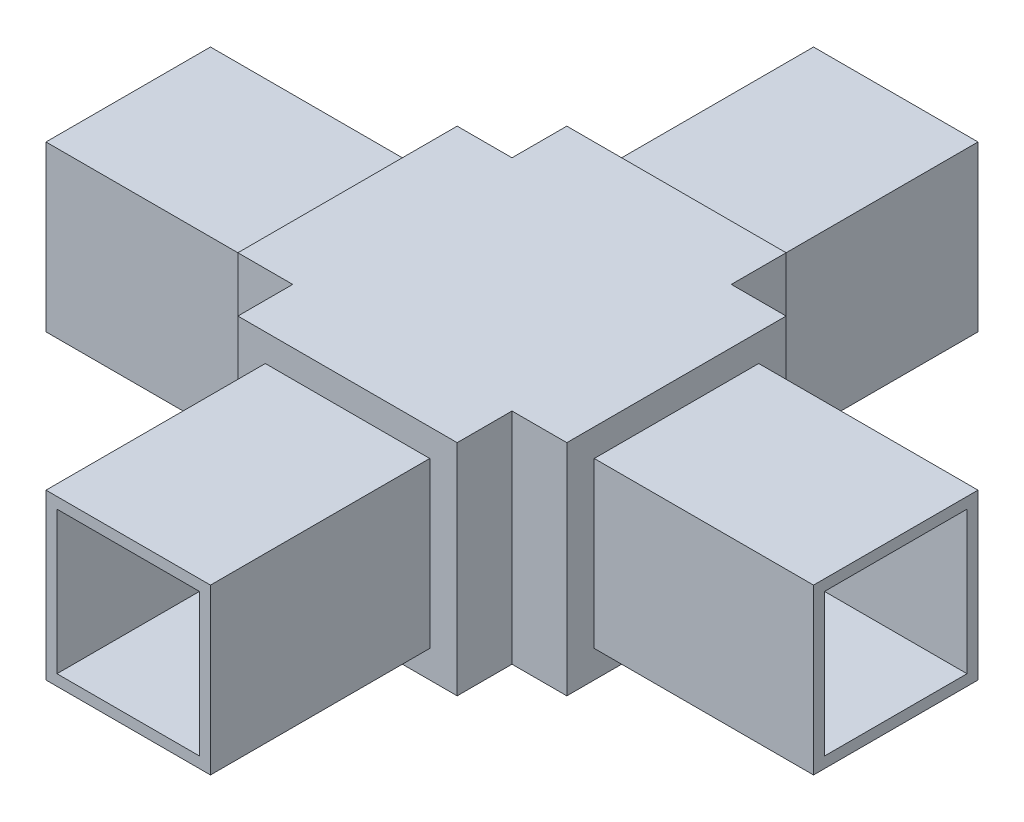
SolidWorks part; units mm, degrees
ref_plane "Alzado" through (0, 0, 0) normal (0, 0, 1) x (1, 0, 0)
ref_plane "Planta" through (0, 0, 0) normal (0, 1, 0) x (1, 0, 0)
ref_plane "Vista lateral" through (0, 0, 0) normal (1, 0, 0) x (0, 0, -1)
sketch "Croquis1" plane through (0, 0, 0) normal (0, 1, 0) x (1, 0, 0)
  line L1 (20, -20) -> (-20, -20)
  line L2 (20, -20) -> (20, 20)
  line L3 (20, 20) -> (-20, 20)
  line L4 (-20, -20) -> (-20, 20)
  line L5 (20, -20) -> (-20, 20) construction
  line L6 (20, 20) -> (-20, -20) construction
  line L7 (20, -20) -> (70, -20)
  line L8 (20, -20) -> (20, 20)
  line L9 (20, 20) -> (70, 20)
  line L10 (70, -20) -> (70, 20)
  line L11 (-20, 20) -> (20, 20)
  line L12 (-20, 20) -> (-20, 70)
  line L13 (-20, 70) -> (20, 70)
  line L14 (20, 20) -> (20, 70)
  line L15 (-20, -20) -> (-70, -20)
  line L16 (-20, -20) -> (-20, 20)
  line L17 (-20, 20) -> (-70, 20)
  line L18 (-70, -20) -> (-70, 20)
  line L19 (-20, -20) -> (20, -20)
  line L20 (-20, -20) -> (-20, -70)
  line L21 (-20, -70) -> (20, -70)
  line L22 (20, -20) -> (20, -70)
  point P0 (0, 0)
  dimension "D1" = 40
  dimension "D2" = 40
  dimension "D3" = 50
  dimension "D4" = 50
  dimension "D5" = 50
  dimension "D6" = 50
extrude "Extruir1" add sketch "Croquis1" along normal blind 40 contours L3 L14 L13 L12 | L4 L1 L2 L3 | L7 L10 L9 L2 | L18 L15 L4 L17 | L22 L1 L20 L21
sketch "Croquis2" plane through (70, 0, 0) normal (1, 0, 0) x (0, 0, -1)
  line L4 (-20, 0) -> (20, 0)
  line L5 (20, 0) -> (20, 40)
  line L6 (20, 40) -> (-20, 40)
  line L7 (-20, 40) -> (-20, 0)
  line L8 (-20, 0) -> (20, 0)
  line L9 (20, 0) -> (20, 40)
  line L10 (20, 40) -> (-20, 40)
  line L11 (-20, 40) -> (-20, 0)
  line L16 (-15, 5) -> (15, 5)
  line L17 (15, 5) -> (15, 35)
  line L18 (15, 35) -> (-15, 35)
  line L19 (-15, 35) -> (-15, 5)
  line L20 (-15, 5) -> (15, 5)
  line L21 (15, 5) -> (15, 35)
  line L22 (15, 35) -> (-15, 35)
  line L23 (-15, 35) -> (-15, 5)
  dimension "D1" = 0
  dimension "D2" = 5
extrude "Extruir2" cut sketch "Croquis2" against normal blind 40
sketch "Croquis3" plane through (0, 0, -70) normal (0, 0, -1) x (-1, 0, 0)
  line L0 (-15, 5) -> (15, 5)
  line L1 (15, 5) -> (15, 35)
  line L2 (15, 35) -> (-15, 35)
  line L3 (-15, 35) -> (-15, 5)
  line L4 (-20, 0) -> (20, 0)
  line L5 (20, 0) -> (20, 40)
  line L6 (20, 40) -> (-20, 40)
  line L7 (-20, 40) -> (-20, 0)
  line L8 (-20, 0) -> (20, 0)
  line L9 (20, 0) -> (20, 40)
  line L10 (20, 40) -> (-20, 40)
  line L11 (-20, 40) -> (-20, 0)
  line L16 (20, 0) -> (20, 40) construction
  dimension "D1" = 0
  dimension "D2" = 5
extrude "Extruir3" cut sketch "Croquis3" against normal blind 40
sketch "Croquis5" plane through (-70, 0, 0) normal (-1, 0, 0) x (0, 0, 1)
  line L0 (-15, 5) -> (15, 5)
  line L1 (15, 5) -> (15, 35)
  line L2 (15, 35) -> (-15, 35)
  line L3 (-15, 35) -> (-15, 5)
  line L4 (-20, 0) -> (20, 0)
  line L5 (20, 0) -> (20, 40)
  line L6 (20, 40) -> (-20, 40)
  line L7 (-20, 40) -> (-20, 0)
  line L8 (-20, 0) -> (20, 0)
  line L9 (20, 0) -> (20, 40)
  line L10 (20, 40) -> (-20, 40)
  line L11 (-20, 40) -> (-20, 0)
  dimension "D1" = 0
  dimension "D2" = 5
extrude "Extruir4" cut sketch "Croquis5" against normal blind 40
sketch "Croquis6" plane through (0, 0, 70) normal (0, 0, 1) x (1, 0, 0)
  line L0 (-15, 5) -> (15, 5)
  line L1 (15, 5) -> (15, 35)
  line L2 (15, 35) -> (-15, 35)
  line L3 (-15, 35) -> (-15, 5)
  line L4 (-20, 0) -> (20, 0)
  line L5 (20, 0) -> (20, 40)
  line L6 (20, 40) -> (-20, 40)
  line L7 (-20, 40) -> (-20, 0)
  line L8 (-20, 0) -> (20, 0)
  line L9 (20, 0) -> (20, 40)
  line L10 (20, 40) -> (-20, 40)
  line L11 (-20, 40) -> (-20, 0)
  dimension "D1" = 0
  dimension "D2" = 5
extrude "Extruir5" cut sketch "Croquis6" against normal blind 40
shell "Vaciado1" thickness 2
